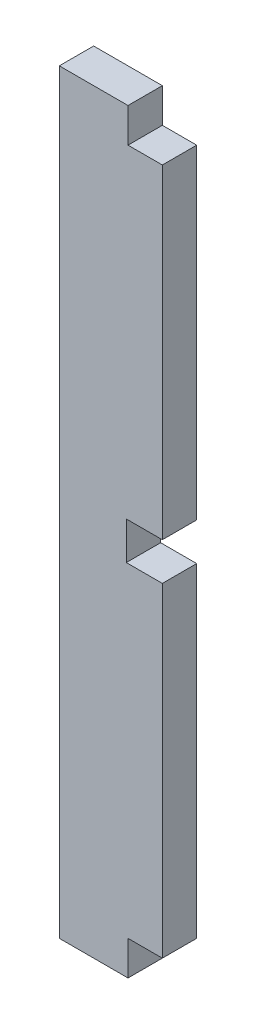
SolidWorks part; units mm, degrees
ref_plane "Front Plane" through (0, 0, 0) normal (0, 0, 1) x (1, 0, 0)
ref_plane "Top Plane" through (0, 0, 0) normal (0, 1, 0) x (1, 0, 0)
ref_plane "Right Plane" through (0, 0, 0) normal (1, 0, 0) x (0, 0, -1)
sketch "Model" plane through (0, 0, 0) normal (0, 0, 1) x (1, 0, 0)
  line L0 (-126.4543, -156.1912) -> (-131.7043, -156.1912)
  line L1 (-126.4543, -208.9412) -> (-131.4543, -208.9412)
  line L2 (-131.4543, -103.9412) -> (-131.4543, -108.9412)
  line L3 (-141.4543, -103.9412) -> (-131.4543, -103.9412)
  line L4 (-126.4543, -161.6912) -> (-126.4543, -208.9412)
  line L5 (-131.7043, -161.6912) -> (-126.4543, -161.6912)
  line L6 (-131.4543, -108.9412) -> (-126.4543, -108.9412)
  line L7 (-141.4543, -213.9412) -> (-141.4543, -103.9412)
  line L8 (-131.4543, -213.9412) -> (-141.4543, -213.9412)
  line L9 (-131.4543, -208.9412) -> (-131.4543, -213.9412)
  line L10 (-131.7043, -156.1912) -> (-131.7043, -161.6912)
  line L11 (-126.4543, -108.9412) -> (-126.4543, -156.1912)
  line L12 (-138.7043, -158.9412) -> (-133.7043, -158.9412)
  line L13 (-135.7043, -159.9412) -> (-133.7043, -158.9412)
  line L14 (-135.7043, -157.9412) -> (-133.7043, -158.9412)
  line L15 (-133.7043, -170.6829) -> (-135.9022, -170.6829)
  line L16 (-135.9022, -170.6829) -> (-135.9022, -169.6651)
  line L17 (-135.9022, -169.6651) -> (-135.8335, -169.1079)
  line L18 (-135.8335, -169.1079) -> (-135.7273, -168.7722)
  line L19 (-135.7273, -168.7722) -> (-135.5931, -168.599)
  line L20 (-135.5931, -168.599) -> (-135.4401, -168.5412)
  line L21 (-135.4401, -168.5412) -> (-134.1851, -168.5412)
  line L22 (-134.1851, -168.5412) -> (-134.0864, -168.5619)
  line L23 (-134.0864, -168.5619) -> (-133.9962, -168.6239)
  line L24 (-133.9962, -168.6239) -> (-133.8417, -168.8721)
  line L25 (-133.8417, -168.8721) -> (-133.7387, -169.2327)
  line L26 (-133.7387, -169.2327) -> (-133.7043, -169.6651)
  line L27 (-133.7043, -169.6651) -> (-133.7043, -170.6829)
  line L28 (-138.0123, -170.6829) -> (-133.7043, -170.6829)
  line L29 (-133.7043, -170.6829) -> (-133.7043, -169.6651)
  line L30 (-133.7043, -169.6651) -> (-133.7387, -169.2327)
  line L31 (-133.7387, -169.2327) -> (-133.8417, -168.8721)
  line L32 (-133.8417, -168.8721) -> (-133.9962, -168.6239)
  line L33 (-133.9962, -168.6239) -> (-134.0864, -168.5619)
  line L34 (-134.0864, -168.5619) -> (-134.1851, -168.5412)
  line L35 (-134.1851, -168.5412) -> (-135.44, -168.5412)
  line L36 (-135.44, -168.5412) -> (-135.5929, -168.599)
  line L37 (-135.5929, -168.599) -> (-135.7272, -168.7722)
  line L38 (-135.7272, -168.7722) -> (-135.8333, -169.1079)
  line L39 (-135.8333, -169.1079) -> (-135.902, -169.6651)
  line L40 (-135.902, -169.6651) -> (-135.966, -169.1141)
  line L41 (-135.966, -169.1141) -> (-136.0706, -168.7722)
  line L42 (-136.0706, -168.7722) -> (-136.2095, -168.599)
  line L43 (-136.2095, -168.599) -> (-136.364, -168.5412)
  line L44 (-136.364, -168.5412) -> (-137.5315, -168.5412)
  line L45 (-137.5315, -168.5412) -> (-137.6252, -168.5619)
  line L46 (-137.6252, -168.5619) -> (-137.7126, -168.6239)
  line L47 (-137.7126, -168.6239) -> (-137.8687, -168.8721)
  line L48 (-137.8687, -168.8721) -> (-137.9764, -169.2359)
  line L49 (-137.9764, -169.2359) -> (-138.0123, -169.6651)
  line L50 (-138.0123, -169.6651) -> (-138.0123, -170.6829)
  line L51 (-135.9018, -169.6651) -> (-135.9018, -170.6829)
  line L52 (-135.9018, -170.6829) -> (-138.0123, -170.6829)
  line L53 (-138.0123, -170.6829) -> (-138.0123, -169.6651)
  line L54 (-138.0123, -169.6651) -> (-137.9764, -169.2359)
  line L55 (-137.9764, -169.2359) -> (-137.8686, -168.8721)
  line L56 (-137.8686, -168.8721) -> (-137.7125, -168.6239)
  line L57 (-137.7125, -168.6239) -> (-137.6251, -168.5619)
  line L58 (-137.6251, -168.5619) -> (-137.5315, -168.5412)
  line L59 (-137.5315, -168.5412) -> (-136.3639, -168.5412)
  line L60 (-136.3639, -168.5412) -> (-136.2093, -168.599)
  line L61 (-136.2093, -168.599) -> (-136.0704, -168.7722)
  line L62 (-136.0704, -168.7722) -> (-135.9658, -169.1141)
  line L63 (-135.9658, -169.1141) -> (-135.9018, -169.6651)
  line L64 (-133.7043, -167.6859) -> (-135.9022, -167.6859)
  line L65 (-135.9022, -167.6859) -> (-135.9022, -166.6682)
  line L66 (-135.9022, -166.6682) -> (-135.8335, -166.1109)
  line L67 (-135.8335, -166.1109) -> (-135.7273, -165.7753)
  line L68 (-135.7273, -165.7753) -> (-135.5931, -165.602)
  line L69 (-135.5931, -165.602) -> (-135.4401, -165.5443)
  line L70 (-135.4401, -165.5443) -> (-134.1851, -165.5443)
  line L71 (-134.1851, -165.5443) -> (-134.0864, -165.5649)
  line L72 (-134.0864, -165.5649) -> (-133.9962, -165.627)
  line L73 (-133.9962, -165.627) -> (-133.8417, -165.8752)
  line L74 (-133.8417, -165.8752) -> (-133.7387, -166.2358)
  line L75 (-133.7387, -166.2358) -> (-133.7043, -166.6682)
  line L76 (-133.7043, -166.6682) -> (-133.7043, -167.6859)
  line L77 (-138.0123, -167.6859) -> (-133.7043, -167.6859)
  line L78 (-133.7043, -167.6859) -> (-133.7043, -166.6682)
  line L79 (-133.7043, -166.6682) -> (-133.7387, -166.2358)
  line L80 (-133.7387, -166.2358) -> (-133.8417, -165.8752)
  line L81 (-133.8417, -165.8752) -> (-133.9962, -165.627)
  line L82 (-133.9962, -165.627) -> (-134.0864, -165.5649)
  line L83 (-134.0864, -165.5649) -> (-134.1851, -165.5443)
  line L84 (-134.1851, -165.5443) -> (-135.44, -165.5443)
  line L85 (-135.44, -165.5443) -> (-135.5929, -165.602)
  line L86 (-135.5929, -165.602) -> (-135.7272, -165.7753)
  line L87 (-135.7272, -165.7753) -> (-135.8333, -166.1109)
  line L88 (-135.8333, -166.1109) -> (-135.902, -166.6682)
  line L89 (-135.902, -166.6682) -> (-135.966, -166.1172)
  line L90 (-135.966, -166.1172) -> (-136.0706, -165.7753)
  line L91 (-136.0706, -165.7753) -> (-136.2095, -165.602)
  line L92 (-136.2095, -165.602) -> (-136.364, -165.5443)
  line L93 (-136.364, -165.5443) -> (-137.5315, -165.5443)
  line L94 (-137.5315, -165.5443) -> (-137.6252, -165.5649)
  line L95 (-137.6252, -165.5649) -> (-137.7126, -165.627)
  line L96 (-137.7126, -165.627) -> (-137.8687, -165.8752)
  line L97 (-137.8687, -165.8752) -> (-137.9764, -166.2389)
  line L98 (-137.9764, -166.2389) -> (-138.0123, -166.6682)
  line L99 (-138.0123, -166.6682) -> (-138.0123, -167.6859)
  line L100 (-135.9018, -166.6682) -> (-135.9018, -167.6859)
  line L101 (-135.9018, -167.6859) -> (-138.0123, -167.6859)
  line L102 (-138.0123, -167.6859) -> (-138.0123, -166.6682)
  line L103 (-138.0123, -166.6682) -> (-137.9764, -166.2389)
  line L104 (-137.9764, -166.2389) -> (-137.8686, -165.8752)
  line L105 (-137.8686, -165.8752) -> (-137.7125, -165.627)
  line L106 (-137.7125, -165.627) -> (-137.6251, -165.5649)
  line L107 (-137.6251, -165.5649) -> (-137.5315, -165.5443)
  line L108 (-137.5315, -165.5443) -> (-136.3639, -165.5443)
  line L109 (-136.3639, -165.5443) -> (-136.2093, -165.602)
  line L110 (-136.2093, -165.602) -> (-136.0704, -165.7753)
  line L111 (-136.0704, -165.7753) -> (-135.9658, -166.1172)
  line L112 (-135.9658, -166.1172) -> (-135.9018, -166.6682)
  line L113 (-133.7043, -163.5651) -> (-133.7395, -164.0061)
  line L114 (-133.7395, -164.0061) -> (-133.8448, -164.3674)
  line L115 (-133.8448, -164.3674) -> (-134.0001, -164.6086)
  line L116 (-134.0001, -164.6086) -> (-134.0889, -164.6689)
  line L117 (-134.0889, -164.6689) -> (-134.1851, -164.689)
  line L118 (-134.1851, -164.689) -> (-134.0889, -164.6689)
  line L119 (-134.0889, -164.6689) -> (-134.0001, -164.6086)
  line L120 (-134.0001, -164.6086) -> (-133.8448, -164.3674)
  line L121 (-133.8448, -164.3674) -> (-133.7395, -164.0061)
  line L122 (-133.7395, -163.1241) -> (-133.8448, -162.7627)
  line L123 (-133.8448, -162.7627) -> (-134.0001, -162.5216)
  line L124 (-134.0001, -162.5216) -> (-134.0889, -162.4613)
  line L125 (-134.0889, -162.4613) -> (-134.1851, -162.4412)
  line L126 (-134.1851, -162.4412) -> (-135.8957, -162.4412)
  line L127 (-135.8957, -162.4412) -> (-135.992, -162.4613)
  line L128 (-135.992, -162.4613) -> (-136.0807, -162.5216)
  line L129 (-136.0807, -162.5216) -> (-136.2361, -162.7627)
  line L130 (-136.2361, -162.7627) -> (-136.3414, -163.1241)
  line L131 (-136.3414, -163.1241) -> (-136.3765, -163.5651)
  line L132 (-136.3765, -163.5651) -> (-136.2766, -164.2394)
  line L133 (-136.2766, -164.2394) -> (-136.1502, -164.4705)
  line L134 (-136.1502, -164.4705) -> (-135.8957, -164.689)
  line L135 (-135.8957, -164.689) -> (-138.0123, -164.689)
  line L136 (-138.0123, -164.689) -> (-138.0123, -162.5161)
  line L137 (-138.0123, -162.5161) -> (-138.0123, -164.689)
  line L138 (-138.0123, -164.689) -> (-135.8957, -164.689)
  line L139 (-135.8957, -164.689) -> (-136.1502, -164.4705)
  line L140 (-136.1502, -164.4705) -> (-136.2766, -164.2394)
  line L141 (-136.2766, -164.2394) -> (-136.3765, -163.5651)
  line L142 (-136.3765, -163.5651) -> (-136.3414, -163.1241)
  line L143 (-136.3414, -163.1241) -> (-136.2361, -162.7627)
  line L144 (-136.2361, -162.7627) -> (-136.0807, -162.5216)
  line L145 (-136.0807, -162.5216) -> (-135.992, -162.4613)
  line L146 (-135.992, -162.4613) -> (-135.8957, -162.4412)
  line L147 (-135.8957, -162.4412) -> (-134.1851, -162.4412)
  line L148 (-134.1851, -162.4412) -> (-134.0889, -162.4613)
  line L149 (-134.0889, -162.4613) -> (-134.0001, -162.5216)
  line L150 (-134.0001, -162.5216) -> (-133.8448, -162.7627)
  line L151 (-133.8448, -162.7627) -> (-133.7395, -163.1241)
  line L152 (-133.7395, -163.1241) -> (-133.7043, -163.5651)
  line L153 (-138.4543, -211.4412) -> (-133.4543, -211.4412)
  line L154 (-135.4543, -212.4412) -> (-133.4543, -211.4412)
  line L155 (-135.4543, -210.4412) -> (-133.4543, -211.4412)
  line L156 (-133.42, -207.9412) -> (-135.6178, -207.9412)
  line L157 (-135.6178, -207.9412) -> (-135.6178, -206.9234)
  line L158 (-135.6178, -206.9234) -> (-135.5492, -206.3662)
  line L159 (-135.5492, -206.3662) -> (-135.443, -206.0305)
  line L160 (-135.443, -206.0305) -> (-135.3088, -205.8573)
  line L161 (-135.3088, -205.8573) -> (-135.1558, -205.7995)
  line L162 (-135.1558, -205.7995) -> (-133.9008, -205.7995)
  line L163 (-133.9008, -205.7995) -> (-133.8021, -205.8202)
  line L164 (-133.8021, -205.8202) -> (-133.7119, -205.8822)
  line L165 (-133.7119, -205.8822) -> (-133.5574, -206.1304)
  line L166 (-133.5574, -206.1304) -> (-133.4544, -206.491)
  line L167 (-133.4544, -206.491) -> (-133.42, -206.9234)
  line L168 (-133.42, -206.9234) -> (-133.42, -207.9412)
  line L169 (-137.7279, -207.9412) -> (-133.42, -207.9412)
  line L170 (-133.42, -207.9412) -> (-133.42, -206.9234)
  line L171 (-133.42, -206.9234) -> (-133.4543, -206.491)
  line L172 (-133.4543, -206.491) -> (-133.5573, -206.1304)
  line L173 (-133.5573, -206.1304) -> (-133.7119, -205.8822)
  line L174 (-133.7119, -205.8822) -> (-133.802, -205.8202)
  line L175 (-133.802, -205.8202) -> (-133.9008, -205.7995)
  line L176 (-133.9008, -205.7995) -> (-135.1557, -205.7995)
  line L177 (-135.1557, -205.7995) -> (-135.3086, -205.8573)
  line L178 (-135.3086, -205.8573) -> (-135.4428, -206.0305)
  line L179 (-135.4428, -206.0305) -> (-135.549, -206.3662)
  line L180 (-135.549, -206.3662) -> (-135.6177, -206.9234)
  line L181 (-135.6177, -206.9234) -> (-135.6816, -206.3724)
  line L182 (-135.6816, -206.3724) -> (-135.7862, -206.0305)
  line L183 (-135.7862, -206.0305) -> (-135.9252, -205.8573)
  line L184 (-135.9252, -205.8573) -> (-136.0797, -205.7995)
  line L185 (-136.0797, -205.7995) -> (-137.2472, -205.7995)
  line L186 (-137.2472, -205.7995) -> (-137.3408, -205.8202)
  line L187 (-137.3408, -205.8202) -> (-137.4282, -205.8822)
  line L188 (-137.4282, -205.8822) -> (-137.5844, -206.1304)
  line L189 (-137.5844, -206.1304) -> (-137.692, -206.4941)
  line L190 (-137.692, -206.4941) -> (-137.7279, -206.9234)
  line L191 (-137.7279, -206.9234) -> (-137.7279, -207.9412)
  line L192 (-135.6175, -206.9234) -> (-135.6175, -207.9412)
  line L193 (-135.6175, -207.9412) -> (-137.7279, -207.9412)
  line L194 (-137.7279, -207.9412) -> (-137.7279, -206.9234)
  line L195 (-137.7279, -206.9234) -> (-137.692, -206.4941)
  line L196 (-137.692, -206.4941) -> (-137.5843, -206.1304)
  line L197 (-137.5843, -206.1304) -> (-137.4282, -205.8822)
  line L198 (-137.4282, -205.8822) -> (-137.3408, -205.8202)
  line L199 (-137.3408, -205.8202) -> (-137.2471, -205.7995)
  line L200 (-137.2471, -205.7995) -> (-136.0795, -205.7995)
  line L201 (-136.0795, -205.7995) -> (-135.925, -205.8573)
  line L202 (-135.925, -205.8573) -> (-135.7861, -206.0305)
  line L203 (-135.7861, -206.0305) -> (-135.6815, -206.3724)
  line L204 (-135.6815, -206.3724) -> (-135.6175, -206.9234)
  line L205 (-133.42, -204.9442) -> (-137.7279, -204.9442)
  line L206 (-137.7279, -204.9442) -> (-137.7279, -203.9264)
  line L207 (-137.7279, -203.9264) -> (-137.692, -203.4925)
  line L208 (-137.692, -203.4925) -> (-137.5844, -203.1272)
  line L209 (-137.5844, -203.1272) -> (-137.4282, -202.8837)
  line L210 (-137.4282, -202.8837) -> (-137.3408, -202.8228)
  line L211 (-137.3408, -202.8228) -> (-137.2472, -202.8025)
  line L212 (-137.2472, -202.8025) -> (-133.9008, -202.8025)
  line L213 (-133.9008, -202.8025) -> (-133.8044, -202.8228)
  line L214 (-133.8044, -202.8228) -> (-133.715, -202.8837)
  line L215 (-133.715, -202.8837) -> (-133.5573, -203.1272)
  line L216 (-133.5573, -203.1272) -> (-133.4543, -203.4831)
  line L217 (-133.4543, -203.4831) -> (-133.42, -203.9264)
  line L218 (-133.42, -203.9264) -> (-133.42, -204.9442)
  line L219 (-137.7279, -204.9442) -> (-133.42, -204.9442)
  line L220 (-133.42, -204.9442) -> (-133.42, -203.9264)
  line L221 (-133.42, -203.9264) -> (-133.4543, -203.4831)
  line L222 (-133.4543, -203.4831) -> (-133.5573, -203.1272)
  line L223 (-133.5573, -203.1272) -> (-133.715, -202.8837)
  line L224 (-133.715, -202.8837) -> (-133.8044, -202.8228)
  line L225 (-133.8044, -202.8228) -> (-133.9008, -202.8025)
  line L226 (-133.9008, -202.8025) -> (-137.2472, -202.8025)
  line L227 (-137.2472, -202.8025) -> (-137.3408, -202.8228)
  line L228 (-137.3408, -202.8228) -> (-137.4282, -202.8837)
  line L229 (-137.4282, -202.8837) -> (-137.5844, -203.1272)
  line L230 (-137.5844, -203.1272) -> (-137.692, -203.4925)
  line L231 (-137.692, -203.4925) -> (-137.7279, -203.9264)
  line L232 (-137.7279, -203.9264) -> (-137.7279, -204.9442)
  line L233 (-133.42, -200.8234) -> (-133.4551, -201.2644)
  line L234 (-133.4551, -201.2644) -> (-133.5605, -201.6257)
  line L235 (-133.5605, -201.6257) -> (-133.7158, -201.8669)
  line L236 (-133.7158, -201.8669) -> (-133.8046, -201.9272)
  line L237 (-133.8046, -201.9272) -> (-133.9008, -201.9473)
  line L238 (-133.9008, -201.9473) -> (-133.8046, -201.9272)
  line L239 (-133.8046, -201.9272) -> (-133.7158, -201.8669)
  line L240 (-133.7158, -201.8669) -> (-133.5605, -201.6257)
  line L241 (-133.5605, -201.6257) -> (-133.4551, -201.2644)
  line L242 (-133.4551, -200.3824) -> (-133.5605, -200.021)
  line L243 (-133.5605, -200.021) -> (-133.7158, -199.7798)
  line L244 (-133.7158, -199.7798) -> (-133.8046, -199.7196)
  line L245 (-133.8046, -199.7196) -> (-133.9008, -199.6995)
  line L246 (-133.9008, -199.6995) -> (-135.6114, -199.6995)
  line L247 (-135.6114, -199.6995) -> (-135.7076, -199.7196)
  line L248 (-135.7076, -199.7196) -> (-135.7964, -199.7798)
  line L249 (-135.7964, -199.7798) -> (-135.9517, -200.021)
  line L250 (-135.9517, -200.021) -> (-136.0571, -200.3824)
  line L251 (-136.0571, -200.3824) -> (-136.0922, -200.8234)
  line L252 (-136.0922, -200.8234) -> (-135.9923, -201.4977)
  line L253 (-135.9923, -201.4977) -> (-135.8659, -201.7287)
  line L254 (-135.8659, -201.7287) -> (-135.6114, -201.9473)
  line L255 (-135.6114, -201.9473) -> (-137.7279, -201.9473)
  line L256 (-137.7279, -201.9473) -> (-137.7279, -199.7744)
  line L257 (-137.7279, -199.7744) -> (-137.7279, -201.9473)
  line L258 (-137.7279, -201.9473) -> (-135.6114, -201.9473)
  line L259 (-135.6114, -201.9473) -> (-135.8659, -201.7287)
  line L260 (-135.8659, -201.7287) -> (-135.9923, -201.4977)
  line L261 (-135.9923, -201.4977) -> (-136.0922, -200.8234)
  line L262 (-136.0922, -200.8234) -> (-136.0571, -200.3824)
  line L263 (-136.0571, -200.3824) -> (-135.9517, -200.021)
  line L264 (-135.9517, -200.021) -> (-135.7964, -199.7798)
  line L265 (-135.7964, -199.7798) -> (-135.7076, -199.7196)
  line L266 (-135.7076, -199.7196) -> (-135.6114, -199.6995)
  line L267 (-135.6114, -199.6995) -> (-133.9008, -199.6995)
  line L268 (-133.9008, -199.6995) -> (-133.8046, -199.7196)
  line L269 (-133.8046, -199.7196) -> (-133.7158, -199.7798)
  line L270 (-133.7158, -199.7798) -> (-133.5605, -200.021)
  line L271 (-133.5605, -200.021) -> (-133.4551, -200.3824)
  line L272 (-133.4551, -200.3824) -> (-133.42, -200.8234)
  line L273 (-129.9543, -126.5034) -> (-130.0246, -127.3854)
  line L274 (-130.0246, -125.6215) -> (-129.9543, -126.5034)
  line L275 (-135.2988, -126.5034) -> (-135.2285, -125.6215)
  line L276 (-135.0178, -124.8987) -> (-135.2285, -125.6215)
  line L277 (-134.3372, -128.7512) -> (-138.5702, -128.7512)
  line L278 (-134.3372, -128.7512) -> (-134.846, -128.3142)
  line L279 (-135.0989, -127.8521) -> (-135.2988, -126.5034)
  line L280 (-134.35, -140.7268) -> (-129.9543, -140.7268)
  line L281 (-138.5702, -124.4055) -> (-138.5702, -128.7512)
  line L282 (-135.0989, -127.8521) -> (-134.846, -128.3142)
  line L283 (-130.7235, -124.2958) -> (-130.9158, -124.2556)
  line L284 (-130.9158, -124.2556) -> (-134.3372, -124.2556)
  line L285 (-134.3372, -124.2556) -> (-134.5296, -124.2958)
  line L286 (-134.5296, -124.2958) -> (-134.7072, -124.4164)
  line L287 (-134.7072, -124.4164) -> (-135.0178, -124.8987)
  line L288 (-130.229, -137.1054) -> (-130.5381, -136.609)
  line L289 (-134.3496, -138.6913) -> (-134.35, -140.7268)
  line L290 (-130.229, -137.1054) -> (-130.023, -137.8266)
  line L291 (-138.5702, -138.6913) -> (-138.4984, -137.8328)
  line L292 (-138.283, -137.1054) -> (-137.9708, -136.609)
  line L293 (-137.9708, -136.609) -> (-137.796, -136.4849)
  line L294 (-130.023, -137.8266) -> (-129.9543, -138.6913)
  line L295 (-137.6087, -136.4435) -> (-135.2737, -136.4435)
  line L296 (-134.2123, -137.5768) -> (-134, -136.9056)
  line L297 (-133.4257, -136.4435) -> (-130.9158, -136.4435)
  line L298 (-134, -136.9056) -> (-133.7315, -136.559)
  line L299 (-138.5702, -140.7268) -> (-138.5702, -138.6913)
  line L300 (-137.796, -136.4849) -> (-137.6087, -136.4435)
  line L301 (-138.5702, -140.7268) -> (-134.35, -140.7268)
  line L302 (-129.9543, -140.7268) -> (-129.9543, -138.6913)
  line L303 (-130.5381, -136.609) -> (-130.7184, -136.4849)
  line L304 (-133.7315, -136.559) -> (-133.4257, -136.4435)
  line L305 (-130.7184, -136.4849) -> (-130.9158, -136.4435)
  line L306 (-134.2123, -137.5768) -> (-134.3496, -138.6913)
  line L307 (-138.4984, -137.8328) -> (-138.283, -137.1054)
  line L308 (-134.9646, -136.559) -> (-135.2737, -136.4435)
  line L309 (-130.0246, -125.6215) -> (-130.2353, -124.8987)
  line L310 (-130.2353, -128.1081) -> (-130.0246, -127.3854)
  line L311 (-130.2353, -124.8987) -> (-130.5459, -124.4164)
  line L312 (-130.5459, -124.4164) -> (-130.7235, -124.2958)
  line L313 (-130.2353, -128.1081) -> (-130.5459, -128.5905)
  line L314 (-134.9646, -136.559) -> (-134.6868, -136.9056)
  line L315 (-138.4984, -133.3624) -> (-138.5702, -132.4851)
  line L316 (-137.9708, -130.3997) -> (-137.796, -130.2779)
  line L317 (-137.6087, -130.2373) -> (-136.9968, -130.2373)
  line L318 (-137.6087, -134.7329) -> (-137.8007, -134.6931)
  line L319 (-137.796, -130.2779) -> (-137.6087, -130.2373)
  line L320 (-137.9708, -130.3997) -> (-138.283, -130.8867)
  line L321 (-130.9158, -134.7329) -> (-130.7184, -134.6931)
  line L322 (-130.7184, -134.6931) -> (-130.5381, -134.5737)
  line L323 (-130.023, -131.5985) -> (-130.229, -130.8867)
  line L324 (-137.8007, -134.6931) -> (-137.9771, -134.5737)
  line L325 (-134.4776, -137.5893) -> (-134.3496, -138.6913)
  line L326 (-130.9158, -134.7329) -> (-137.6087, -134.7329)
  line L327 (-138.4984, -131.6173) -> (-138.283, -130.8867)
  line L328 (-130.5381, -134.5737) -> (-130.229, -134.096)
  line L329 (-137.9771, -134.5737) -> (-138.283, -134.096)
  line L330 (-134.6868, -136.9056) -> (-134.4776, -137.5893)
  line L331 (-129.9543, -132.4851) -> (-130.023, -133.3749)
  line L332 (-130.229, -130.8867) -> (-130.5444, -130.3997)
  line L333 (-130.9158, -130.2373) -> (-131.5277, -130.2373)
  line L334 (-138.283, -134.096) -> (-138.4984, -133.3624)
  line L335 (-138.4984, -131.6173) -> (-138.5702, -132.4851)
  line L336 (-130.5444, -130.3997) -> (-130.7231, -130.2779)
  line L337 (-130.5459, -128.5905) -> (-130.7235, -128.711)
  line L338 (-130.7235, -128.711) -> (-130.9158, -128.7512)
  line L339 (-130.023, -133.3749) -> (-130.229, -134.096)
  line L340 (-129.9543, -132.4851) -> (-130.023, -131.5985)
  line L341 (-130.7231, -130.2779) -> (-130.9158, -130.2373)
  line L342 (-128.9543, -140.7268) -> (-128.9543, -124.4055)
  line L343 (-138.4543, -106.4412) -> (-133.4543, -106.4412)
  line L344 (-135.4543, -107.4412) -> (-133.4543, -106.4412)
  line L345 (-135.4543, -105.4412) -> (-133.4543, -106.4412)
  line L346 (-133.42, -118.1829) -> (-135.6178, -118.1829)
  line L347 (-135.6178, -118.1829) -> (-135.6178, -117.1651)
  line L348 (-135.6178, -117.1651) -> (-135.5492, -116.6079)
  line L349 (-135.5492, -116.6079) -> (-135.443, -116.2722)
  line L350 (-135.443, -116.2722) -> (-135.3088, -116.099)
  line L351 (-135.3088, -116.099) -> (-135.1558, -116.0412)
  line L352 (-135.1558, -116.0412) -> (-133.9008, -116.0412)
  line L353 (-133.9008, -116.0412) -> (-133.8021, -116.0619)
  line L354 (-133.8021, -116.0619) -> (-133.7119, -116.1239)
  line L355 (-133.7119, -116.1239) -> (-133.5574, -116.3721)
  line L356 (-133.5574, -116.3721) -> (-133.4544, -116.7327)
  line L357 (-133.4544, -116.7327) -> (-133.42, -117.1651)
  line L358 (-133.42, -117.1651) -> (-133.42, -118.1829)
  line L359 (-137.7279, -118.1829) -> (-133.42, -118.1829)
  line L360 (-133.42, -118.1829) -> (-133.42, -117.1651)
  line L361 (-133.42, -117.1651) -> (-133.4543, -116.7327)
  line L362 (-133.4543, -116.7327) -> (-133.5573, -116.3721)
  line L363 (-133.5573, -116.3721) -> (-133.7119, -116.1239)
  line L364 (-133.7119, -116.1239) -> (-133.802, -116.0619)
  line L365 (-133.802, -116.0619) -> (-133.9008, -116.0412)
  line L366 (-133.9008, -116.0412) -> (-135.1557, -116.0412)
  line L367 (-135.1557, -116.0412) -> (-135.3086, -116.099)
  line L368 (-135.3086, -116.099) -> (-135.4428, -116.2722)
  line L369 (-135.4428, -116.2722) -> (-135.549, -116.6079)
  line L370 (-135.549, -116.6079) -> (-135.6177, -117.1651)
  line L371 (-135.6177, -117.1651) -> (-135.6816, -116.6141)
  line L372 (-135.6816, -116.6141) -> (-135.7862, -116.2722)
  line L373 (-135.7862, -116.2722) -> (-135.9252, -116.099)
  line L374 (-135.9252, -116.099) -> (-136.0797, -116.0412)
  line L375 (-136.0797, -116.0412) -> (-137.2472, -116.0412)
  line L376 (-137.2472, -116.0412) -> (-137.3408, -116.0619)
  line L377 (-137.3408, -116.0619) -> (-137.4282, -116.1239)
  line L378 (-137.4282, -116.1239) -> (-137.5844, -116.3721)
  line L379 (-137.5844, -116.3721) -> (-137.692, -116.7359)
  line L380 (-137.692, -116.7359) -> (-137.7279, -117.1651)
  line L381 (-137.7279, -117.1651) -> (-137.7279, -118.1829)
  line L382 (-135.6175, -117.1651) -> (-135.6175, -118.1829)
  line L383 (-135.6175, -118.1829) -> (-137.7279, -118.1829)
  line L384 (-137.7279, -118.1829) -> (-137.7279, -117.1651)
  line L385 (-137.7279, -117.1651) -> (-137.692, -116.7359)
  line L386 (-137.692, -116.7359) -> (-137.5843, -116.3721)
  line L387 (-137.5843, -116.3721) -> (-137.4282, -116.1239)
  line L388 (-137.4282, -116.1239) -> (-137.3408, -116.0619)
  line L389 (-137.3408, -116.0619) -> (-137.2471, -116.0412)
  line L390 (-137.2471, -116.0412) -> (-136.0795, -116.0412)
  line L391 (-136.0795, -116.0412) -> (-135.925, -116.099)
  line L392 (-135.925, -116.099) -> (-135.7861, -116.2722)
  line L393 (-135.7861, -116.2722) -> (-135.6815, -116.6141)
  line L394 (-135.6815, -116.6141) -> (-135.6175, -117.1651)
  line L395 (-133.42, -115.1859) -> (-137.7279, -115.1859)
  line L396 (-137.7279, -115.1859) -> (-137.7279, -114.1682)
  line L397 (-137.7279, -114.1682) -> (-137.692, -113.7342)
  line L398 (-137.692, -113.7342) -> (-137.5844, -113.3689)
  line L399 (-137.5844, -113.3689) -> (-137.4282, -113.1254)
  line L400 (-137.4282, -113.1254) -> (-137.3408, -113.0645)
  line L401 (-137.3408, -113.0645) -> (-137.2472, -113.0443)
  line L402 (-137.2472, -113.0443) -> (-133.9008, -113.0443)
  line L403 (-133.9008, -113.0443) -> (-133.8044, -113.0645)
  line L404 (-133.8044, -113.0645) -> (-133.715, -113.1254)
  line L405 (-133.715, -113.1254) -> (-133.5573, -113.3689)
  line L406 (-133.5573, -113.3689) -> (-133.4543, -113.7249)
  line L407 (-133.4543, -113.7249) -> (-133.42, -114.1682)
  line L408 (-133.42, -114.1682) -> (-133.42, -115.1859)
  line L409 (-137.7279, -115.1859) -> (-133.42, -115.1859)
  line L410 (-133.42, -115.1859) -> (-133.42, -114.1682)
  line L411 (-133.42, -114.1682) -> (-133.4543, -113.7249)
  line L412 (-133.4543, -113.7249) -> (-133.5573, -113.3689)
  line L413 (-133.5573, -113.3689) -> (-133.715, -113.1254)
  line L414 (-133.715, -113.1254) -> (-133.8044, -113.0645)
  line L415 (-133.8044, -113.0645) -> (-133.9008, -113.0443)
  line L416 (-133.9008, -113.0443) -> (-137.2472, -113.0443)
  line L417 (-137.2472, -113.0443) -> (-137.3408, -113.0645)
  line L418 (-137.3408, -113.0645) -> (-137.4282, -113.1254)
  line L419 (-137.4282, -113.1254) -> (-137.5844, -113.3689)
  line L420 (-137.5844, -113.3689) -> (-137.692, -113.7342)
  line L421 (-137.692, -113.7342) -> (-137.7279, -114.1682)
  line L422 (-137.7279, -114.1682) -> (-137.7279, -115.1859)
  line L423 (-133.42, -111.0651) -> (-133.4551, -111.5061)
  line L424 (-133.4551, -111.5061) -> (-133.5605, -111.8674)
  line L425 (-133.5605, -111.8674) -> (-133.7158, -112.1086)
  line L426 (-133.7158, -112.1086) -> (-133.8046, -112.1689)
  line L427 (-133.8046, -112.1689) -> (-133.9008, -112.189)
  line L428 (-133.9008, -112.189) -> (-133.8046, -112.1689)
  line L429 (-133.8046, -112.1689) -> (-133.7158, -112.1086)
  line L430 (-133.7158, -112.1086) -> (-133.5605, -111.8674)
  line L431 (-133.5605, -111.8674) -> (-133.4551, -111.5061)
  line L432 (-133.4551, -110.6241) -> (-133.5605, -110.2627)
  line L433 (-133.5605, -110.2627) -> (-133.7158, -110.0216)
  line L434 (-133.7158, -110.0216) -> (-133.8046, -109.9613)
  line L435 (-133.8046, -109.9613) -> (-133.9008, -109.9412)
  line L436 (-133.9008, -109.9412) -> (-135.6114, -109.9412)
  line L437 (-135.6114, -109.9412) -> (-135.7076, -109.9613)
  line L438 (-135.7076, -109.9613) -> (-135.7964, -110.0216)
  line L439 (-135.7964, -110.0216) -> (-135.9517, -110.2627)
  line L440 (-135.9517, -110.2627) -> (-136.0571, -110.6241)
  line L441 (-136.0571, -110.6241) -> (-136.0922, -111.0651)
  line L442 (-136.0922, -111.0651) -> (-135.9923, -111.7394)
  line L443 (-135.9923, -111.7394) -> (-135.8659, -111.9705)
  line L444 (-135.8659, -111.9705) -> (-135.6114, -112.189)
  line L445 (-135.6114, -112.189) -> (-137.7279, -112.189)
  line L446 (-137.7279, -112.189) -> (-137.7279, -110.0161)
  line L447 (-137.7279, -110.0161) -> (-137.7279, -112.189)
  line L448 (-137.7279, -112.189) -> (-135.6114, -112.189)
  line L449 (-135.6114, -112.189) -> (-135.8659, -111.9705)
  line L450 (-135.8659, -111.9705) -> (-135.9923, -111.7394)
  line L451 (-135.9923, -111.7394) -> (-136.0922, -111.0651)
  line L452 (-136.0922, -111.0651) -> (-136.0571, -110.6241)
  line L453 (-136.0571, -110.6241) -> (-135.9517, -110.2627)
  line L454 (-135.9517, -110.2627) -> (-135.7964, -110.0216)
  line L455 (-135.7964, -110.0216) -> (-135.7076, -109.9613)
  line L456 (-135.7076, -109.9613) -> (-135.6114, -109.9412)
  line L457 (-135.6114, -109.9412) -> (-133.9008, -109.9412)
  line L458 (-133.9008, -109.9412) -> (-133.8046, -109.9613)
  line L459 (-133.8046, -109.9613) -> (-133.7158, -110.0216)
  line L460 (-133.7158, -110.0216) -> (-133.5605, -110.2627)
  line L461 (-133.5605, -110.2627) -> (-133.4551, -110.6241)
  line L462 (-133.4551, -110.6241) -> (-133.42, -111.0651)
sketch "Sketch1" plane through (0, 0, 0) normal (0, 0, 1) x (1, 0, 0)
  line L0 (-131.4543, -213.9412) -> (-141.4543, -213.9412) construction
  line L1 (-131.4543, -208.9412) -> (-131.4543, -213.9412) construction
  line L2 (-126.4543, -208.9412) -> (-131.4543, -208.9412) construction
  line L3 (-126.4543, -161.6912) -> (-126.4543, -208.9412) construction
  line L4 (-131.7043, -161.6912) -> (-126.4543, -161.6912) construction
  line L5 (-131.7043, -156.1912) -> (-131.7043, -161.6912) construction
  line L6 (-126.4543, -156.1912) -> (-131.7043, -156.1912) construction
  line L7 (-126.4543, -108.9412) -> (-126.4543, -156.1912) construction
  line L8 (-131.4543, -108.9412) -> (-126.4543, -108.9412) construction
  line L9 (-131.4543, -103.9412) -> (-131.4543, -108.9412) construction
  line L10 (-141.4543, -103.9412) -> (-131.4543, -103.9412) construction
  line L11 (-141.4543, -213.9412) -> (-141.4543, -103.9412) construction
  line L12 (-131.4543, -213.9412) -> (-141.4543, -213.9412)
  line L13 (-131.4543, -208.9412) -> (-131.4543, -213.9412)
  line L14 (-126.4543, -208.9412) -> (-131.4543, -208.9412)
  line L15 (-126.4543, -161.6912) -> (-126.4543, -208.9412)
  line L16 (-131.7043, -161.6912) -> (-126.4543, -161.6912)
  line L17 (-131.7043, -156.1912) -> (-131.7043, -161.6912)
  line L18 (-126.4543, -156.1912) -> (-131.7043, -156.1912)
  line L19 (-126.4543, -108.9412) -> (-126.4543, -156.1912)
  line L20 (-131.4543, -108.9412) -> (-126.4543, -108.9412)
  line L21 (-131.4543, -103.9412) -> (-131.4543, -108.9412)
  line L22 (-141.4543, -103.9412) -> (-131.4543, -103.9412)
  line L23 (-141.4543, -213.9412) -> (-141.4543, -103.9412)
extrude "Boss-Extrude1" add sketch "Sketch1" along normal mid plane 5
ref_plane "Plane1" through (0, -158.9412, 0) normal (0, 1, 0) x (1, 0, 0)
